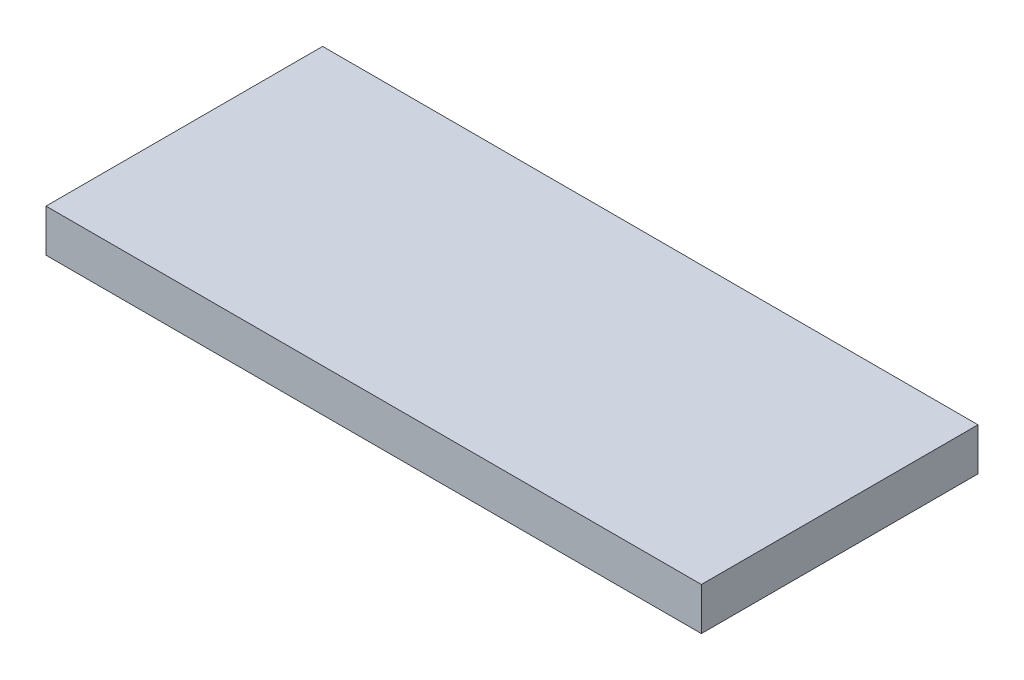
SolidWorks part; units mm, degrees
ref_plane "Front Plane" through (0, 0, 0) normal (0, 0, 1) x (1, 0, 0)
ref_plane "Top Plane" through (0, 0, 0) normal (0, 1, 0) x (1, 0, 0)
ref_plane "Right Plane" through (0, 0, 0) normal (1, 0, 0) x (0, 0, -1)
sketch "Sketch1" plane through (0, 0, 0) normal (0, 1, 0) x (1, 0, 0)
  line L1 (77, 32.5) -> (-77, 32.5)
  line L2 (77, 32.5) -> (77, -32.5)
  line L3 (77, -32.5) -> (-77, -32.5)
  line L4 (-77, 32.5) -> (-77, -32.5)
  line L5 (77, 32.5) -> (-77, -32.5) construction
  line L6 (77, -32.5) -> (-77, 32.5) construction
  point P0 (0, 0)
  dimension "D1" = 154
  dimension "D2" = 65
extrude "base" add sketch "Sketch1" along normal blind 10 contours L1 L4 L3 L2
sketch "Sketch2" plane through (0, 0, 0) normal (0, -1, 0) x (1, 0, 0)
  circle A0 centre (0, 0) radius 3
  dimension "D1" = 6
extrude "load cell button cut" [suppressed] cut sketch "Sketch2" against normal blind 2
sketch "Sketch4" plane through (0, 0, 0) normal (1, 0, 0) x (0, 0, -1)
  line L0 (3, 0) -> (3, 2)
  line L1 (3, 2) -> (0, 3.7321)
  line L2 (0, 3.7321) -> (0, 0) construction
  line L3 (0, 0) -> (3, 0)
  line L4 (0, 3.7321) -> (0, 0)
  dimension "D1" = 3
  dimension "D2" = 2
  dimension "D3" = 60
revolve "Cut-Revolve1" [suppressed] cut sketch "Sketch4" angle 360 about L2
sketch "Sketch5" plane through (0, 0, 32.5) normal (0, 0, 1) x (1, 0, 0)
  line L0 (-77, 10) -> (-71.2265, 0)
  line L1 (77, 0) -> (-77, 0) construction
  line L2 (-71.2265, 0) -> (-71.2265, 10) construction
  line L3 (77, 10) -> (-77, 10) construction
  line L4 (-77, 10) -> (-77, 0)
  line L5 (-77, 0) -> (-71.2265, 0)
  dimension "D1" = 30
extrude "Cut-Extrude1" [suppressed] cut sketch "Sketch5" against normal through all
fillet "Fillet1" [suppressed] radius 0.5
equation "\"D2@Sketch1\"=65"
equation "\"D1@Sketch1\"=144+10"
